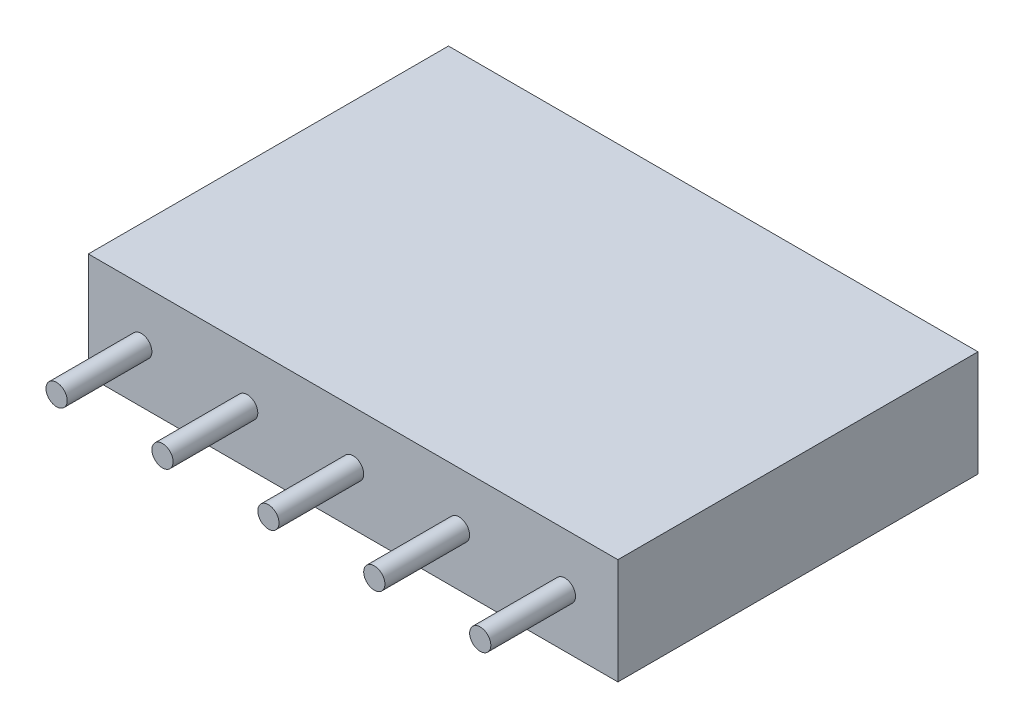
SolidWorks part; units mm, degrees
ref_plane "Plan de face" through (0, 0, 0) normal (0, 0, 1) x (1, 0, 0)
ref_plane "Plan de dessus" through (0, 0, 0) normal (0, 1, 0) x (1, 0, 0)
ref_plane "Plan de droite" through (0, 0, 0) normal (1, 0, 0) x (0, 0, -1)
sketch "Esquisse1" plane through (0, 0, 0) normal (0, 0, 1) x (1, 0, 0)
  line L1 (0, 0) -> (-2.5, 0)
  line L2 (0, 0) -> (0, 2.5)
  line L3 (0, 2.5) -> (-2.5, 2.5)
  line L4 (-2.5, 0) -> (-2.5, 2.5)
  dimension "D1" = 2.5
  dimension "D2" = 2.5
extrude "Boss.-Extru.1" add sketch "Esquisse1" along normal blind 8.5
sketch "Esquisse2" plane through (0, 0, 8.5) normal (0, 0, 1) x (1, 0, 0)
  line L0 (-2.5, 2.5) -> (0, 0) construction
  circle A0 centre (-1.25, 1.25) radius 0.25
  dimension "D1" = 0.5
extrude "Boss.-Extru.2" add sketch "Esquisse2" along normal blind 2
sketch "Esquisse3" plane through (0, 0, 0) normal (0, 0, -1) x (-1, 0, 0)
  line L0 (0, 2.5) -> (2.5, 0) construction
  circle A0 centre (1.25, 1.25) radius 0.25
  dimension "D1" = 0.5
extrude "Enlèv. mat.-Extru.2" cut sketch "Esquisse3" against normal blind 4
pattern_linear "Répétition linéaire1" count 5 spacing 2.5 along (-1, 0, 0) of "Boss.-Extru.1", "Enlèv. mat.-Extru.2", "Boss.-Extru.2"
